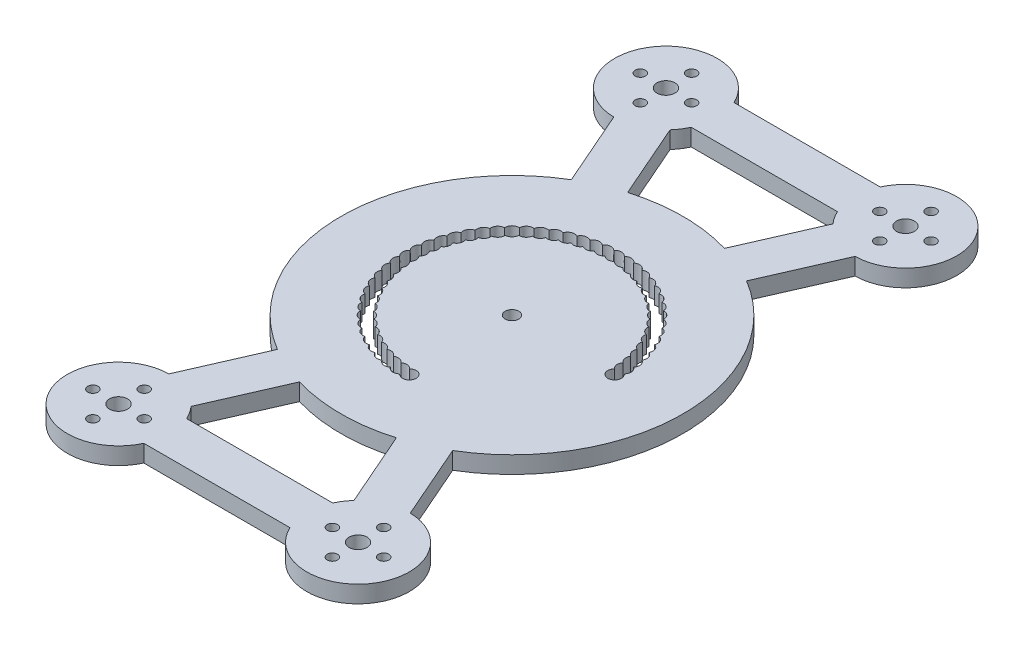
SolidWorks part; units mm, degrees
ref_plane "Front Plane" through (0, 0, 0) normal (0, 0, 1) x (1, 0, 0)
ref_plane "Top Plane" through (0, 0, 0) normal (0, 1, 0) x (1, 0, 0)
ref_plane "Right Plane" through (0, 0, 0) normal (1, 0, 0) x (0, 0, -1)
sketch "Sketch1" plane through (0, 0, 0) normal (0, 1, 0) x (1, 0, 0)
  line L1 (-50, -95) -> (50, -95)
  line L2 (-50, -95) -> (-50, 95)
  line L3 (-50, 95) -> (50, 95)
  line L4 (50, -95) -> (50, 95)
  line L5 (-50, -95) -> (50, 95) construction
  line L6 (-50, 95) -> (50, -95) construction
  point P0 (0, 0)
  dimension "D1" = 100
  dimension "D2" = 190
extrude "Boss-Extrude1" add sketch "Sketch1" along normal blind 5
sketch "Sketch2" plane through (0, 5, 0) normal (0, 1, 0) x (1, 0, 0)
  line L0 (0, 95) -> (0, -95) construction
  line L1 (50, 95) -> (-50, 95) construction
  line L2 (-50, -95) -> (50, -95) construction
  line L3 (-50, 0) -> (50, 0) construction
  line L4 (-50, 95) -> (-50, -95) construction
  line L5 (50, -95) -> (50, 95) construction
  line L6 (0, 0) -> (50, 0) construction
  line L7 (0, 0) -> (30, 0) construction
  circle A0 centre (0, 0) radius 2
  arc A1 (30, 0) -> (0, 30) centre (0, 0) ccw construction
  arc A31 (28.5755, 1.4038) -> (31.2801, 1.5367) centre (30, 0) ccw
  arc A33 (31.2801, 1.5367) -> (30.9788, 4.5953) centre (29.8555, 2.9405) ccw
  arc A34 (30.9788, 4.5953) -> (30.3792, 7.6096) centre (29.4236, 5.8527) ccw
  arc A35 (30.3792, 7.6096) -> (29.4871, 10.5506) centre (28.7082, 8.7085) ccw
  arc A36 (29.4871, 10.5506) -> (28.311, 13.3901) centre (27.7164, 11.4805) ccw
  arc A37 (28.311, 13.3901) -> (26.8622, 16.1006) centre (26.4576, 14.1419) ccw
  arc A38 (26.8622, 16.1006) -> (25.1547, 18.656) centre (24.9441, 16.6671) ccw
  arc A39 (25.1547, 18.656) -> (23.205, 21.0317) centre (23.1903, 19.0318) ccw
  arc A40 (23.205, 21.0317) -> (21.0317, 23.205) centre (21.2132, 21.2132) ccw
  arc A41 (21.0317, 23.205) -> (18.656, 25.1547) centre (19.0318, 23.1903) ccw
  arc A42 (18.656, 25.1547) -> (16.1006, 26.8622) centre (16.6671, 24.9441) ccw
  arc A43 (16.1006, 26.8622) -> (13.3901, 28.311) centre (14.1419, 26.4576) ccw
  arc A44 (13.3901, 28.311) -> (10.5506, 29.4871) centre (11.4805, 27.7164) ccw
  arc A45 (10.5506, 29.4871) -> (7.6096, 30.3792) centre (8.7085, 28.7082) ccw
  arc A46 (7.6096, 30.3792) -> (4.5953, 30.9788) centre (5.8527, 29.4236) ccw
  arc A47 (1.4038, 28.5755) -> (4.1979, 28.3003) centre (2.9405, 29.8555) ccw
  arc A48 (-1.4038, 28.5755) -> (1.4038, 28.5755) centre (0, 30) ccw
  arc A49 (-4.1979, 28.3003) -> (-1.4038, 28.5755) centre (-2.9405, 29.8555) ccw
  arc A50 (-6.9516, 27.7525) -> (-4.1979, 28.3003) centre (-5.8527, 29.4236) ccw
  arc A51 (-9.6384, 26.9375) -> (-6.9516, 27.7525) centre (-8.7085, 28.7082) ccw
  arc A52 (-12.2323, 25.8631) -> (-9.6384, 26.9375) centre (-11.4805, 27.7164) ccw
  arc A53 (-14.7084, 24.5396) -> (-12.2323, 25.8631) centre (-14.1419, 26.4576) ccw
  arc A54 (-17.0429, 22.9797) -> (-14.7084, 24.5396) centre (-16.6671, 24.9441) ccw
  arc A55 (-19.2133, 21.1986) -> (-17.0429, 22.9797) centre (-19.0318, 23.1903) ccw
  arc A56 (-21.1986, 19.2133) -> (-19.2133, 21.1986) centre (-21.2132, 21.2132) ccw
  arc A57 (-22.9797, 17.0429) -> (-21.1986, 19.2133) centre (-23.1903, 19.0318) ccw
  arc A58 (-24.5396, 14.7084) -> (-22.9797, 17.0429) centre (-24.9441, 16.6671) ccw
  arc A59 (-25.8631, 12.2323) -> (-24.5396, 14.7084) centre (-26.4576, 14.1419) ccw
  arc A60 (-26.9375, 9.6384) -> (-25.8631, 12.2323) centre (-27.7164, 11.4805) ccw
  arc A61 (-29.4871, 10.5506) -> (-30.3792, 7.6096) centre (-28.7082, 8.7085) ccw
  arc A62 (-28.3003, 4.1979) -> (-27.7525, 6.9516) centre (-29.4236, 5.8527) ccw
  arc A63 (-28.5755, 1.4038) -> (-28.3003, 4.1979) centre (-29.8555, 2.9405) ccw
  arc A64 (-28.5755, -1.4038) -> (-28.5755, 1.4038) centre (-30, 0) ccw
  arc A65 (-28.3003, -4.1979) -> (-28.5755, -1.4038) centre (-29.8555, -2.9405) ccw
  arc A66 (-27.7525, -6.9516) -> (-28.3003, -4.1979) centre (-29.4236, -5.8527) ccw
  arc A67 (-26.9375, -9.6384) -> (-27.7525, -6.9516) centre (-28.7082, -8.7085) ccw
  arc A68 (-25.8631, -12.2323) -> (-26.9375, -9.6384) centre (-27.7164, -11.4805) ccw
  arc A69 (-24.5396, -14.7084) -> (-25.8631, -12.2323) centre (-26.4576, -14.1419) ccw
  arc A70 (-22.9797, -17.0429) -> (-24.5396, -14.7084) centre (-24.9441, -16.6671) ccw
  arc A71 (-21.1986, -19.2133) -> (-22.9797, -17.0429) centre (-23.1903, -19.0318) ccw
  arc A72 (-19.2133, -21.1986) -> (-21.1986, -19.2133) centre (-21.2132, -21.2132) ccw
  arc A73 (-17.0429, -22.9797) -> (-19.2133, -21.1986) centre (-19.0318, -23.1903) ccw
  arc A74 (-14.7084, -24.5396) -> (-17.0429, -22.9797) centre (-16.6671, -24.9441) ccw
  arc A75 (-12.2323, -25.8631) -> (-14.7084, -24.5396) centre (-14.1419, -26.4576) ccw
  arc A76 (-9.6384, -26.9375) -> (-12.2323, -25.8631) centre (-11.4805, -27.7164) ccw
  arc A77 (-6.9516, -27.7525) -> (-9.6384, -26.9375) centre (-8.7085, -28.7082) ccw
  arc A78 (-4.1979, -28.3003) -> (-6.9516, -27.7525) centre (-5.8527, -29.4236) ccw
  arc A79 (-1.4038, -28.5755) -> (-4.1979, -28.3003) centre (-2.9405, -29.8555) ccw
  arc A80 (-1.5367, -31.2801) -> (-1.4038, -28.5755) centre (0, -30) ccw
  arc A81 (-4.5953, -30.9788) -> (-1.5367, -31.2801) centre (-2.9405, -29.8555) ccw
  arc A82 (-7.6096, -30.3792) -> (-4.5953, -30.9788) centre (-5.8527, -29.4236) ccw
  arc A83 (-10.5506, -29.4871) -> (-7.6096, -30.3792) centre (-8.7085, -28.7082) ccw
  arc A84 (-13.3901, -28.311) -> (-10.5506, -29.4871) centre (-11.4805, -27.7164) ccw
  arc A85 (-16.1006, -26.8622) -> (-13.3901, -28.311) centre (-14.1419, -26.4576) ccw
  arc A86 (-18.656, -25.1547) -> (-16.1006, -26.8622) centre (-16.6671, -24.9441) ccw
  arc A87 (-21.0317, -23.205) -> (-18.656, -25.1547) centre (-19.0318, -23.1903) ccw
  arc A88 (-23.205, -21.0317) -> (-21.0317, -23.205) centre (-21.2132, -21.2132) ccw
  arc A89 (-25.1547, -18.656) -> (-23.205, -21.0317) centre (-23.1903, -19.0318) ccw
  arc A90 (-26.8622, -16.1006) -> (-25.1547, -18.656) centre (-24.9441, -16.6671) ccw
  arc A91 (-28.311, -13.3901) -> (-26.8622, -16.1006) centre (-26.4576, -14.1419) ccw
  arc A92 (-29.4871, -10.5506) -> (-28.311, -13.3901) centre (-27.7164, -11.4805) ccw
  arc A93 (-30.3792, -7.6096) -> (-29.4871, -10.5506) centre (-28.7082, -8.7085) ccw
  arc A94 (-30.9788, -4.5953) -> (-30.3792, -7.6096) centre (-29.4236, -5.8527) ccw
  arc A95 (-31.2801, -1.5367) -> (-30.9788, -4.5953) centre (-29.8555, -2.9405) ccw
  arc A96 (-31.2801, 1.5367) -> (-31.2801, -1.5367) centre (-30, 0) ccw
  arc A97 (-30.9788, 4.5953) -> (-31.2801, 1.5367) centre (-29.8555, 2.9405) ccw
  arc A98 (-30.3792, 7.6096) -> (-30.9788, 4.5953) centre (-29.4236, 5.8527) ccw
  arc A99 (-27.7525, 6.9516) -> (-26.9375, 9.6384) centre (-28.7082, 8.7085) ccw
  arc A100 (-28.311, 13.3901) -> (-29.4871, 10.5506) centre (-27.7164, 11.4805) ccw
  arc A101 (-26.8622, 16.1006) -> (-28.311, 13.3901) centre (-26.4576, 14.1419) ccw
  arc A102 (-25.1547, 18.656) -> (-26.8622, 16.1006) centre (-24.9441, 16.6671) ccw
  arc A103 (-23.205, 21.0317) -> (-25.1547, 18.656) centre (-23.1903, 19.0318) ccw
  arc A104 (-21.0317, 23.205) -> (-23.205, 21.0317) centre (-21.2132, 21.2132) ccw
  arc A105 (-18.656, 25.1547) -> (-21.0317, 23.205) centre (-19.0318, 23.1903) ccw
  arc A106 (-16.1006, 26.8622) -> (-18.656, 25.1547) centre (-16.6671, 24.9441) ccw
  arc A107 (-13.3901, 28.311) -> (-16.1006, 26.8622) centre (-14.1419, 26.4576) ccw
  arc A108 (28.3003, 4.1979) -> (28.5755, 1.4038) centre (29.8555, 2.9405) ccw
  arc A109 (27.7525, 6.9516) -> (28.3003, 4.1979) centre (29.4236, 5.8527) ccw
  arc A110 (26.9375, 9.6384) -> (27.7525, 6.9516) centre (28.7082, 8.7085) ccw
  arc A111 (25.8631, 12.2323) -> (26.9375, 9.6384) centre (27.7164, 11.4805) ccw
  arc A112 (24.5396, 14.7084) -> (25.8631, 12.2323) centre (26.4576, 14.1419) ccw
  arc A113 (22.9797, 17.0429) -> (24.5396, 14.7084) centre (24.9441, 16.6671) ccw
  arc A114 (21.1986, 19.2133) -> (22.9797, 17.0429) centre (23.1903, 19.0318) ccw
  arc A115 (19.2133, 21.1986) -> (21.1986, 19.2133) centre (21.2132, 21.2132) ccw
  arc A116 (17.0429, 22.9797) -> (19.2133, 21.1986) centre (19.0318, 23.1903) ccw
  arc A117 (-10.5506, 29.4871) -> (-13.3901, 28.311) centre (-11.4805, 27.7164) ccw
  arc A118 (14.7084, 24.5396) -> (17.0429, 22.9797) centre (16.6671, 24.9441) ccw
  arc A119 (-7.6096, 30.3792) -> (-10.5506, 29.4871) centre (-8.7085, 28.7082) ccw
  arc A120 (12.2323, 25.8631) -> (14.7084, 24.5396) centre (14.1419, 26.4576) ccw
  arc A121 (-4.5953, 30.9788) -> (-7.6096, 30.3792) centre (-5.8527, 29.4236) ccw
  arc A122 (-1.5367, 31.2801) -> (-4.5953, 30.9788) centre (-2.9405, 29.8555) ccw
  arc A123 (9.6384, 26.9375) -> (12.2323, 25.8631) centre (11.4805, 27.7164) ccw
  arc A124 (6.9516, 27.7525) -> (9.6384, 26.9375) centre (8.7085, 28.7082) ccw
  arc A125 (1.5367, 31.2801) -> (-1.5367, 31.2801) centre (0, 30) ccw
  arc A126 (4.5953, 30.9788) -> (1.5367, 31.2801) centre (2.9405, 29.8555) ccw
  arc A127 (4.1979, 28.3003) -> (6.9516, 27.7525) centre (5.8527, 29.4236) ccw
  point P19 (0, 0)
  point P20 (0, 0)
  point P119 (0, 0)
  point P120 (0, 0)
  point P121 (0, 0)
  point P122 (0, 0)
  point P123 (0, 0)
  point P124 (0, 0)
  point P125 (0, 0)
  point P126 (0, 0)
  point P127 (0, 0)
  point P128 (0, 0)
  point P129 (0, 0)
  point P130 (0, 0)
  point P131 (0, 0)
  point P132 (0, 0)
  point P133 (0, 0)
  point P134 (0, 0)
  dimension "D2" = 4
  dimension "D3" = 30
  dimension "D1" = 0
  dimension "D5" = 30
  dimension "D4" = 49
extrude "Cut-Extrude1" cut sketch "Sketch2" against normal through all
sketch "Sketch3" plane through (0, 5, 0) normal (0, 1, 0) x (1, 0, 0)
  line L0 (-35, 80) -> (-35, 87.5) construction
  line L1 (0, 0) -> (0, -95) construction
  line L2 (50, 95) -> (-50, 95) construction
  line L3 (-50, -95) -> (50, -95) construction
  line L4 (-50, 0) -> (50, 0) construction
  line L5 (-50, 95) -> (-50, -95) construction
  line L6 (50, -95) -> (50, 95) construction
  line L19 (0, 0) -> (0, 95) construction
  line L29 (0, 0) -> (-35, 80) construction
  line L30 (-23.8085, 70.0125) -> (-14.1578, 47.9537)
  line L31 (-35.2605, 65.0023) -> (-25.6097, 42.9435)
  line L32 (23.8085, 70.0125) -> (14.1578, 47.9537)
  line L33 (0, 0) -> (35, 80) construction
  line L34 (35.2605, 65.0023) -> (25.6097, 42.9435)
  line L35 (-35.2605, -65.0023) -> (-25.6097, -42.9435)
  line L36 (0, 0) -> (-35, -80) construction
  line L37 (-23.8085, -70.0125) -> (-14.1578, -47.9537)
  line L38 (23.8085, -70.0125) -> (14.1578, -47.9537)
  line L39 (0, 0) -> (35, -80) construction
  line L40 (35.2605, -65.0023) -> (25.6097, -42.9435)
  line L41 (-35, 80) -> (35, 80) construction
  line L42 (-21.3641, 86.25) -> (21.3641, 86.25)
  line L43 (-21.3641, 73.75) -> (21.3641, 73.75)
  line L44 (-21.3641, -86.25) -> (21.3641, -86.25)
  line L45 (-35, -80) -> (35, -80) construction
  line L46 (-21.3641, -73.75) -> (21.3641, -73.75)
  circle A1 centre (-35, 80) radius 2.625
  circle A2 centre (-35, 87.5) radius 1.5
  circle A3 centre (-27.5, 80) radius 1.5
  circle A4 centre (-35, 72.5) radius 1.5
  circle A5 centre (-42.5, 80) radius 1.5
  circle A6 centre (-35, 80) radius 7.5 construction
  circle A7 centre (35, 72.5) radius 1.5
  circle A8 centre (42.5, 80) radius 1.5
  circle A9 centre (27.5, 80) radius 1.5
  circle A10 centre (35, 87.5) radius 1.5
  circle A11 centre (35, 80) radius 2.625
  circle A12 centre (-35, -72.5) radius 1.5
  circle A13 centre (-42.5, -80) radius 1.5
  circle A14 centre (-35, -80) radius 2.625
  circle A15 centre (-35, -87.5) radius 1.5
  circle A16 centre (-27.5, -80) radius 1.5
  circle A17 centre (27.5, -80) radius 1.5
  circle A18 centre (35, -87.5) radius 1.5
  circle A19 centre (42.5, -80) radius 1.5
  circle A20 centre (35, -80) radius 2.625
  circle A21 centre (35, -72.5) radius 1.5
  arc A30 (14.1578, 47.9537) -> (-14.1578, 47.9537) centre (0, 0) ccw
  arc A31 (-23.8085, 70.0125) -> (-21.3641, 73.75) centre (-35, 80) ccw
  arc A32 (23.8085, 70.0125) -> (21.3641, 73.75) centre (35, 80) cw
  arc A33 (-23.8085, -70.0125) -> (-21.3641, -73.75) centre (-35, -80) cw
  arc A34 (23.8085, -70.0125) -> (21.3641, -73.75) centre (35, -80) ccw
  arc A35 (-25.6097, 42.9435) -> (-25.6097, -42.9435) centre (0, 0) ccw
  arc A36 (-14.1578, -47.9537) -> (14.1578, -47.9537) centre (0, 0) ccw
  arc A37 (25.6097, -42.9435) -> (25.6097, 42.9435) centre (0, 0) ccw
  arc A38 (-21.3641, -86.25) -> (-35.2605, -65.0023) centre (-35, -80) cw
  arc A39 (21.3641, -86.25) -> (35.2605, -65.0023) centre (35, -80) ccw
  arc A40 (21.3641, 86.25) -> (35.2605, 65.0023) centre (35, 80) cw
  arc A41 (-21.3641, 86.25) -> (-35.2605, 65.0023) centre (-35, 80) ccw
  dimension "D1" = 5.25
  dimension "D4" = 3
  dimension "D7" = 12.5
  dimension "D2" = 15
  dimension "D3" = 15
  dimension "D6" = 7.5
  dimension "D8" = 12.5
  dimension "D5" = 4
extrude "Cut-Extrude2" cut sketch "Sketch3" against normal through all flip side to cut
